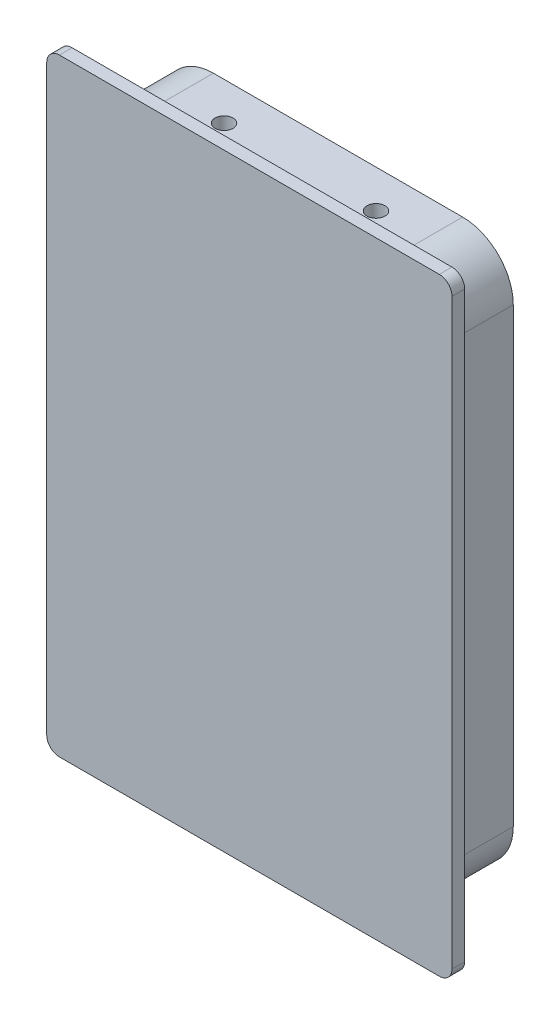
SolidWorks part; units mm, degrees
material "POM Acetal Copolymer"
ref_plane "Front Plane" through (0, 0, 0) normal (0, 0, 1) x (1, 0, 0)
ref_plane "Top Plane" through (0, 0, 0) normal (0, 1, 0) x (1, 0, 0)
ref_plane "Right Plane" through (0, 0, 0) normal (1, 0, 0) x (0, 0, -1)
sketch "Sketch1" plane through (0, 0, 0) normal (0, 0, 1) x (1, 0, 0)
  line L1 (-25.4, -38.1) -> (25.4, -38.1)
  line L2 (-25.4, -38.1) -> (-25.4, 38.1)
  line L3 (-25.4, 38.1) -> (25.4, 38.1)
  line L4 (25.4, -38.1) -> (25.4, 38.1)
  line L5 (-25.4, -38.1) -> (25.4, 38.1) construction
  line L6 (-25.4, 38.1) -> (25.4, -38.1) construction
  point P0 (0, 0)
  dimension "D1" = 76.2
  dimension "D2" = 50.8
extrude "Boss-Extrude1" add sketch "Sketch1" along normal blind 1.5875
sketch "Sketch2" plane through (0, 0, 0) normal (0, 0, -1) x (-1, 0, 0)
  line L1 (-21.971, -34.671) -> (21.971, -34.671)
  line L2 (-21.971, -34.671) -> (-21.971, 34.671)
  line L3 (-21.971, 34.671) -> (21.971, 34.671)
  line L4 (21.971, -34.671) -> (21.971, 34.671)
  line L5 (-21.971, -34.671) -> (21.971, 34.671) construction
  line L6 (-21.971, 34.671) -> (21.971, -34.671) construction
  point P0 (0, 0)
  dimension "D1" = 69.342
  dimension "D2" = 43.942
extrude "Boss-Extrude2" add sketch "Sketch2" along normal blind 9.525
fillet "Fillet1" radius 6.35 4 edges at (21.971, -34.671, -4.7625) (-21.971, -34.671, -4.7625) (-21.971, 34.671, -4.7625) (21.971, 34.671, -4.7625)
sketch "Sketch3" plane through (0, 0, -9.525) normal (0, 0, -1) x (-1, 0, 0)
  line L8 (-18.796, 28.321) -> (-18.796, -28.321)
  line L9 (-15.621, -31.496) -> (15.621, -31.496)
  line L10 (18.796, -28.321) -> (18.796, 28.321)
  line L11 (15.621, 31.496) -> (-15.621, 31.496)
  line L12 (-18.796, 28.321) -> (-18.796, -28.321)
  line L13 (-15.621, -31.496) -> (15.621, -31.496)
  line L14 (18.796, -28.321) -> (18.796, 28.321)
  line L15 (15.621, 31.496) -> (-15.621, 31.496)
  arc A8 (-18.796, -28.321) -> (-15.621, -31.496) centre (-15.621, -28.321) ccw
  arc A9 (15.621, -31.496) -> (18.796, -28.321) centre (15.621, -28.321) ccw
  arc A10 (18.796, 28.321) -> (15.621, 31.496) centre (15.621, 28.321) ccw
  arc A11 (-15.621, 31.496) -> (-18.796, 28.321) centre (-15.621, 28.321) ccw
  arc A12 (-18.796, -28.321) -> (-15.621, -31.496) centre (-15.621, -28.321) ccw
  arc A13 (15.621, -31.496) -> (18.796, -28.321) centre (15.621, -28.321) ccw
  arc A14 (18.796, 28.321) -> (15.621, 31.496) centre (15.621, 28.321) ccw
  arc A15 (-15.621, 31.496) -> (-18.796, 28.321) centre (-15.621, 28.321) ccw
  dimension "D1" = 3.175
extrude "Cut-Extrude1" cut sketch "Sketch3" against normal up to surface (9.525 mm away) up to face at (0, 0, 0)
hole_wizard "#4-40 Tapped Hole1" positions "Sketch6" profile "Sketch7" tap size "#4-40" standard "Ansi Inch"
sketch "Sketch6" plane through (0, 34.671, 0) normal (0, 1, 0) x (-1, 0, 0)
  line L0 (-15.621, -4.7625) -> (15.621, -4.7625) construction
  line L1 (-15.621, 0) -> (-15.621, -9.525) construction
  line L2 (15.621, -9.525) -> (15.621, 0) construction
  point P0 (-9.525, -4.7625)
  point P1 (9.525, -4.7625)
  dimension "D1" = 19.05
  dimension "D2" = 9.525
sketch "Sketch7" plane through (9.525, 34.671, -4.7625) normal (1, 0, 0) x (0, 0, 1)
  line L0 (0, 0) -> (0, 69.342)
  line L1 (0, 69.342) -> (1.1303, 69.342)
  line L2 (1.1303, 69.342) -> (1.1303, 0)
  line L5 (1.1303, 0) -> (0, 0)
  line L11 (0, -6.35) -> (0, 107.95) construction
  dimension "Thru Tap Drill Dia." = 2.2606
  dimension "Thru Tap Drill Depth" = 69.342
cosmetic thread "Hole Thread1" parameters "D2"=2.8448
cosmetic thread "Hole Thread2" parameters "D2"=2.8448
mirror "Mirror1" about plane through (0, 0, 0) normal (0, 1, 0) of "#4-40 Tapped Hole1"
fillet "Fillet2" radius 1.5875 4 edges at (-25.4, -38.1, 0.7937) (25.4, -38.1, 0.7937) (25.4, 38.1, 0.7937) (-25.4, 38.1, 0.7937)
